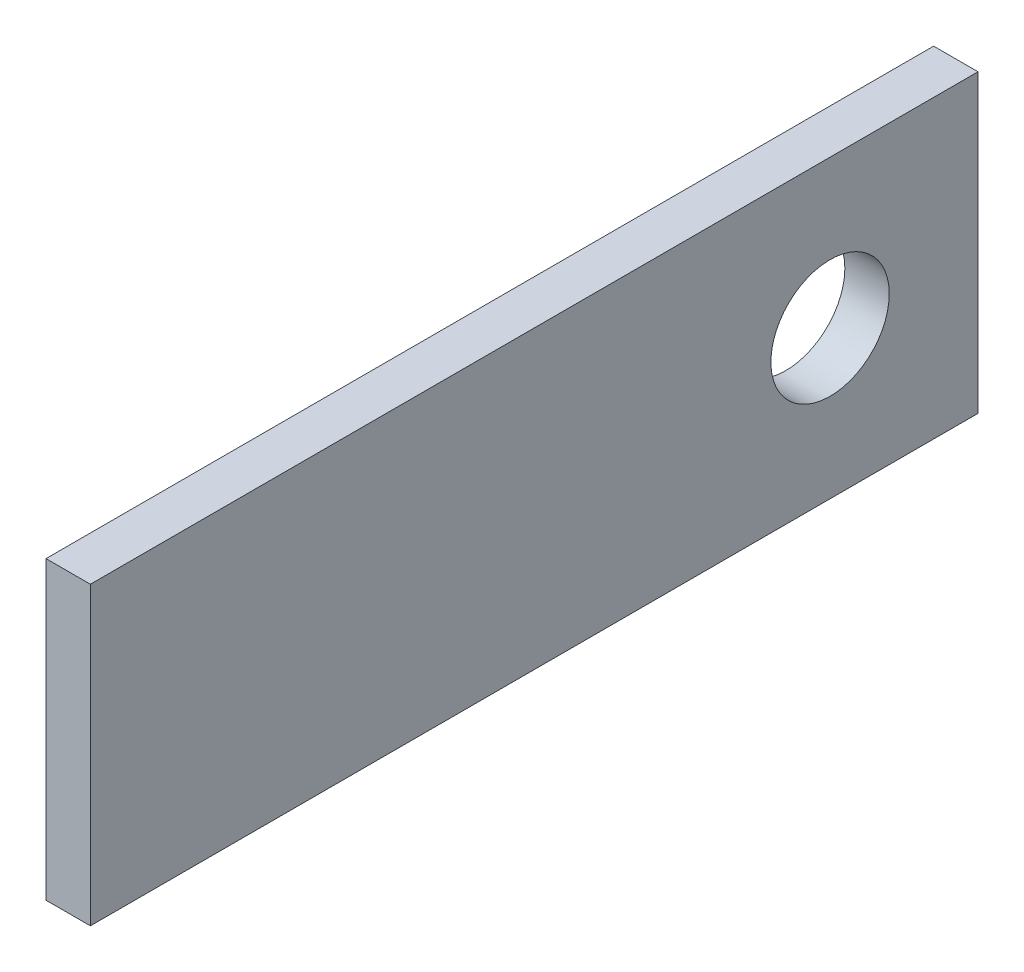
SolidWorks part; units mm, degrees
ref_plane "Front Plane" through (0, 0, 0) normal (0, 0, 1) x (1, 0, 0)
ref_plane "Top Plane" through (0, 0, 0) normal (0, 1, 0) x (1, 0, 0)
ref_plane "Right Plane" through (0, 0, 0) normal (1, 0, 0) x (0, 0, -1)
sketch "Sketch1" plane through (0, 0, 0) normal (1, 0, 0) x (0, 0, -1)
  line L0 (0, 0) -> (60, 0) construction
  line L1 (-60, -20) -> (60, -20)
  line L2 (-60, -20) -> (-60, 20)
  line L3 (-60, 20) -> (60, 20)
  line L4 (60, -20) -> (60, 20)
  line L5 (-60, -20) -> (60, 20) construction
  line L6 (-60, 20) -> (60, -20) construction
  circle A1 centre (40, 0) radius 8
  dimension "D1" = 40
  dimension "D3" = 16
  dimension "D2" = 120
  dimension "D4" = 20
extrude "Boss-Extrude1" add sketch "Sketch1" along normal blind 6
